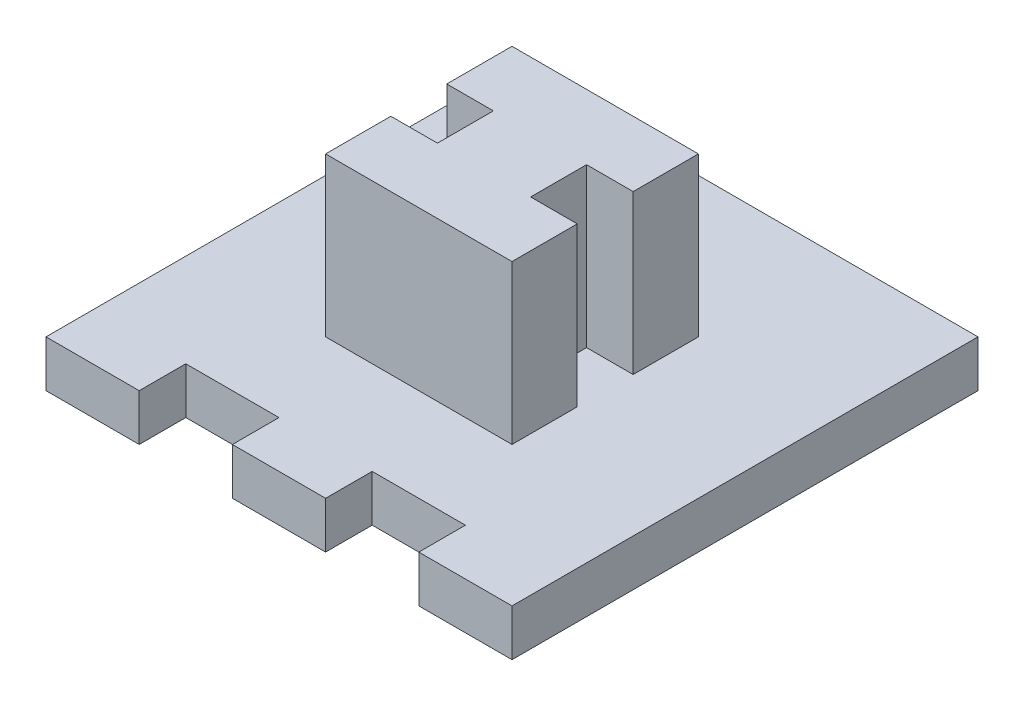
SolidWorks part; units mm, degrees
ref_plane "Front" through (0, 0, 0) normal (0, 0, 1) x (1, 0, 0)
ref_plane "Top" through (0, 0, 0) normal (0, 1, 0) x (1, 0, 0)
ref_plane "Right" through (0, 0, 0) normal (1, 0, 0) x (0, 0, -1)
sketch "Sketch1" plane through (0, 0, 0) normal (0, 1, 0) x (1, 0, 0)
  line L1 (-50, 50) -> (50, 50)
  line L2 (-50, 50) -> (-50, -50)
  line L3 (-50, -50) -> (50, -50)
  line L4 (50, 50) -> (50, -50)
  line L5 (-50, 50) -> (50, -50) construction
  line L6 (-50, -50) -> (50, 50) construction
  point P0 (0, 0)
extrude "Boss-Extrude1" add sketch "Sketch1" along normal blind 10
sketch "Sketch6" plane through (0, 10, 0) normal (0, 1, 0) x (1, 0, 0)
  line L1 (-20, 20) -> (20, 20)
  line L2 (-20, 20) -> (-20, -20)
  line L3 (-20, -20) -> (20, -20)
  line L4 (20, 20) -> (20, -20)
  line L5 (-20, 20) -> (20, -20) construction
  line L6 (-20, -20) -> (20, 20) construction
  point P0 (0, 0)
  dimension "D1" = 40
  dimension "D2" = 40
extrude "Boss-Extrude3" add sketch "Sketch6" along normal blind 34
sketch "Sketch8" plane through (0, 10, 0) normal (0, 1, 0) x (1, 0, 0)
  line L0 (-50, -50) -> (50, -50) construction
  line L1 (-30, -40) -> (-10, -40)
  line L2 (-30, -40) -> (-30, -50)
  line L3 (-30, -50) -> (-10, -50)
  line L4 (-10, -40) -> (-10, -50)
extrude "Cut-Extrude1" cut sketch "Sketch8" against normal blind 10
sketch "Sketch9" plane through (0, 10, 0) normal (0, 1, 0) x (1, 0, 0)
  line L0 (-10, -50) -> (50, -50) construction
  line L1 (10, -50) -> (30, -50)
  line L2 (10, -50) -> (10, -40)
  line L3 (10, -40) -> (30, -40)
  line L4 (30, -50) -> (30, -40)
extrude "Cut-Extrude2" cut sketch "Sketch9" against normal blind 10
sketch "Sketch10" plane through (0, 44, 0) normal (0, 1, 0) x (1, 0, 0)
  line L0 (20, -20) -> (20, 20) construction
  line L1 (20, 6) -> (10, 6)
  line L2 (20, 6) -> (20, -6)
  line L3 (20, -6) -> (10, -6)
  line L4 (10, 6) -> (10, -6)
  line L5 (-20, 20) -> (-20, -20) construction
  line L6 (-20, 6) -> (-10, 6)
  line L7 (-20, 6) -> (-20, -6)
  line L8 (-20, -6) -> (-10, -6)
  line L9 (-10, 6) -> (-10, -6)
  dimension "D1" = 12
extrude "Cut-Extrude3" cut sketch "Sketch10" against normal blind 34
